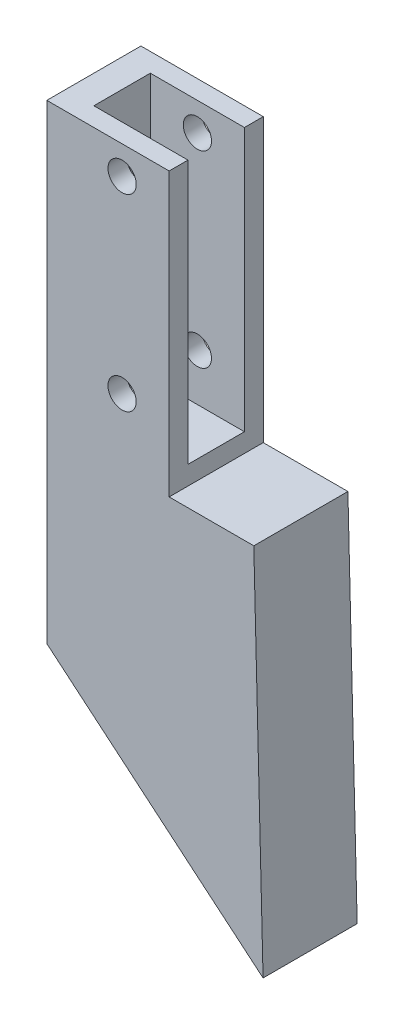
SolidWorks part; units mm, degrees
ref_plane "前视基准面" through (0, 0, 0) normal (0, 0, 1) x (1, 0, 0)
ref_plane "上视基准面" through (0, 0, 0) normal (0, 1, 0) x (1, 0, 0)
ref_plane "右视基准面" through (0, 0, 0) normal (1, 0, 0) x (0, 0, -1)
sketch "草图1" plane through (0, 0, 0) normal (0, 0, 1) x (1, 0, 0)
  line L0 (-6.5, -15) -> (-6.5, -35)
  line L1 (6.5, -15) -> (-6.5, -15)
  line L2 (6.5, -15) -> (6.5, 15)
  line L3 (6.5, 15) -> (-6.5, 15)
  line L4 (-6.5, -15) -> (-6.5, 15)
  line L5 (6.5, -15) -> (-6.5, 15) construction
  line L6 (6.5, 15) -> (-6.5, -15) construction
  line L7 (-6.5, -35) -> (16.4813, -54.2836)
  line L8 (16.4813, -54.2836) -> (15.4956, -15)
  line L9 (15.4956, -15) -> (6.5, -15)
  point P0 (0, 0)
  dimension "D1" = 30
  dimension "D2" = 20
  dimension "D3" = 13
  dimension "D4" = 130
  dimension "D5" = 30
extrude "凸台-拉伸1" add sketch "草图1" along normal blind 10 contours L4 L1 L2 L3 | L8 L9 L1 L0 L7
sketch "草图2" plane through (6.5, 0, 0) normal (1, 0, 0) x (0, 0, -1)
  line L0 (-5, 15) -> (-5, -15) construction
  line L1 (-10, 15) -> (0, 15) construction
  line L2 (-10, -15) -> (0, -15) construction
  line L4 (-2, -13) -> (-8, -13)
  line L5 (-2, -13) -> (-2, 15)
  line L6 (-2, 15) -> (-8, 15)
  line L7 (-8, -13) -> (-8, 15)
  line L8 (-2, -13) -> (-8, 15) construction
  line L9 (-2, 15) -> (-8, -13) construction
  point P6 (-5, 1)
  dimension "D1" = 6
  dimension "D2" = 28
extrude "切除-拉伸1" cut sketch "草图2" against normal blind 10
sketch "草图3" plane through (0, 0, 10) normal (0, 0, 1) x (1, 0, 0)
  line L0 (6.5, 15) -> (1.5, 15) construction
  line L1 (6.5, 15) -> (-6.5, 15) construction
  line L2 (1.5, 15) -> (1.5, 12) construction
  circle A0 centre (1.5, 12) radius 1.5
  dimension "D3" = 3
  dimension "D1" = 5
  dimension "D2" = 3
extrude "切除-拉伸2" cut sketch "草图3" against normal through all
sketch "草图4" plane through (0, 0, 10) normal (0, 0, 1) x (1, 0, 0)
  line L0 (1.5, 12) -> (1.5, -8) construction
  circle A0 centre (1.5, -8) radius 1.5
  dimension "D1" = 3
  dimension "D2" = 20
extrude "切除-拉伸3" cut sketch "草图4" against normal through all
